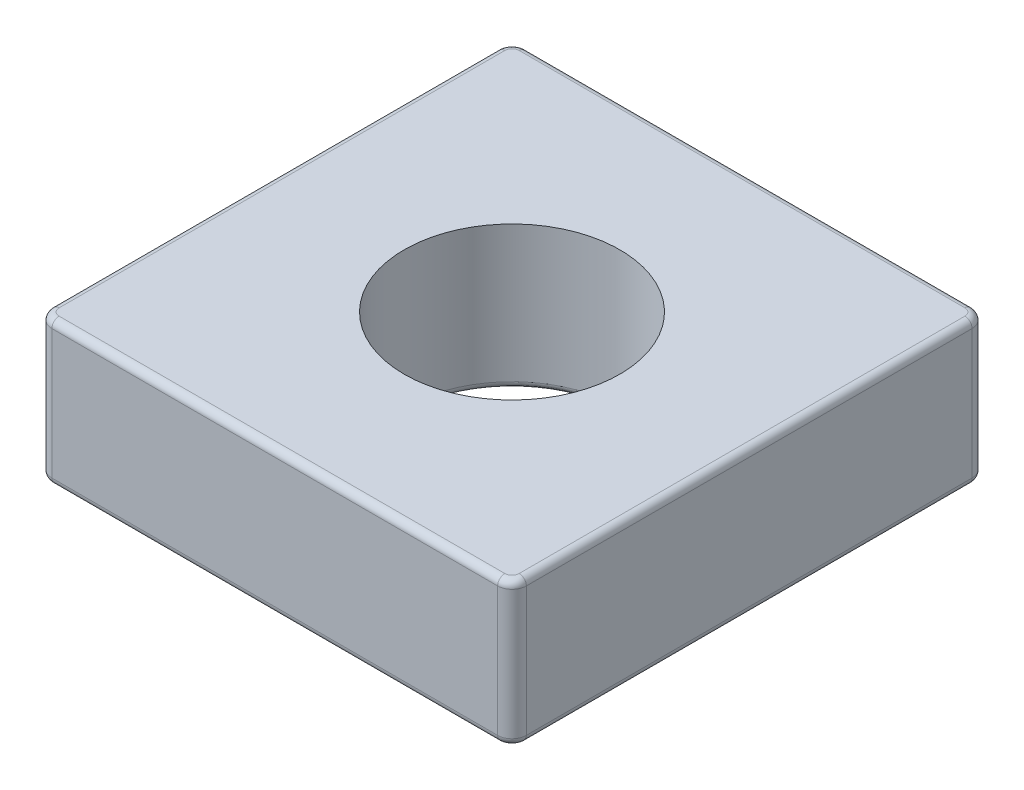
SolidWorks part; units mm, degrees
ref_plane "前视基准面" through (0, 0, 0) normal (0, 0, 1) x (1, 0, 0)
ref_plane "上视基准面" through (0, 0, 0) normal (0, 1, 0) x (1, 0, 0)
ref_plane "右视基准面" through (0, 0, 0) normal (1, 0, 0) x (0, 0, -1)
sketch "草图1" plane through (0, 0, 0) normal (0, 1, 0) x (1, 0, 0)
  line L0 (-4.5206, 0) -> (6.2145, 0) construction
  line L1 (-3.3, 3.3) -> (3.3, 3.3)
  line L2 (-3.3, 3.3) -> (-3.3, -3.3)
  line L3 (-3.3, -3.3) -> (3.3, -3.3)
  line L4 (3.3, 3.3) -> (3.3, -3.3)
  line L5 (0, 4.8021) -> (0, -6.0831) construction
  dimension "D1" = 6.6
  dimension "D2" = 6.6
extrude "凸台-拉伸1" add sketch "草图1" along normal blind 2
sketch "草图2" plane through (0, 2, 0) normal (0, 1, 0) x (1, 0, 0)
  circle A0 centre (0, 0) radius 1.5
  dimension "D1" = 3
extrude "切除-拉伸1" cut sketch "草图2" against normal blind 2
fillet "圆角1" radius 0.2 4 edges at (-3.3, 1, -3.3) (3.3, 1, -3.3) (3.3, 1, 3.3) (-3.3, 1, 3.3)
fillet "圆角2" radius 0.1 17 edges at (-3.2414, 2, 3.2414) (-3.3, 2, 0) (-3.2414, 2, -3.2414) (0, 2, -3.3) (3.2414, 2, -3.2414) (3.3, 2, 0) (3.2414, 2, 3.2414) (-3.2414, 0, 3.2414) (0, 0, 3.3) (3.2414, 0, 3.2414) (3.3, 0, 0) (3.2414, 0, -3.2414) (0, 0, -3.3) (-3.2414, 0, -3.2414) (-3.3, 0, 0) (0, 0, 1.5) (0, 2, 3.3)
